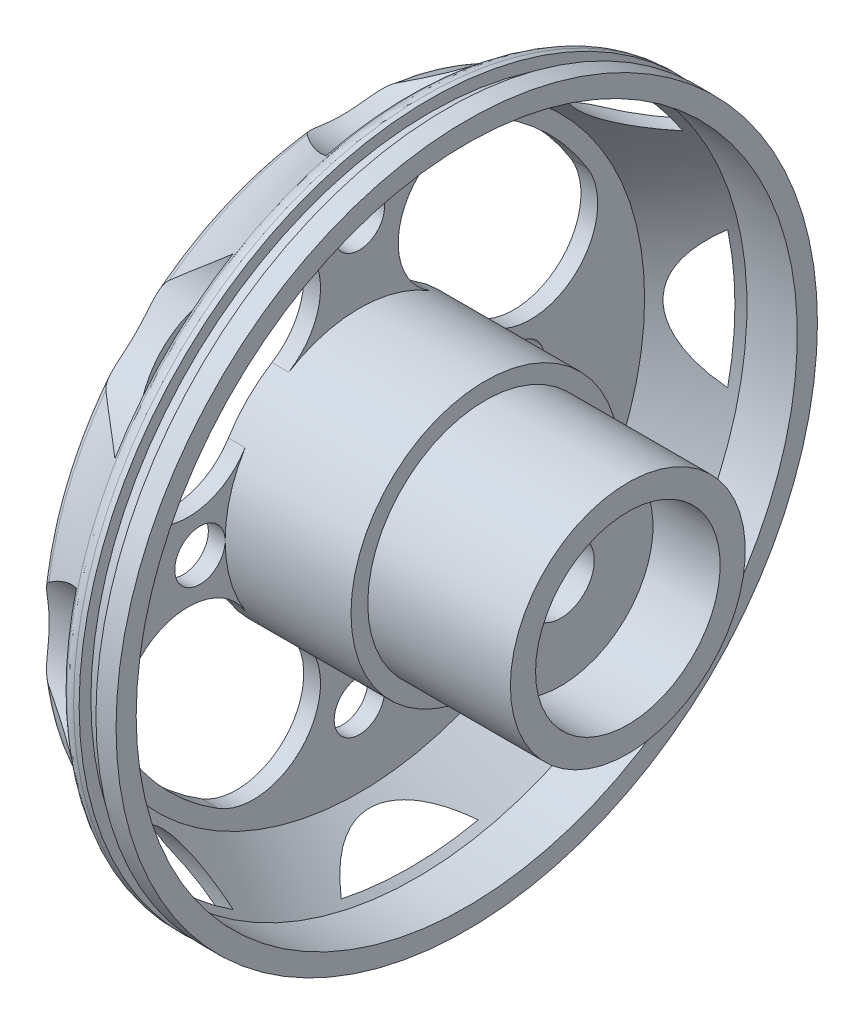
SolidWorks part; units mm, degrees
material "Aleación 1060"
ref_plane "Alzado" through (0, 0, 0) normal (0, 0, 1) x (1, 0, 0)
ref_plane "Planta" through (0, 0, 0) normal (0, 1, 0) x (1, 0, 0)
ref_plane "Vista lateral" through (0, 0, 0) normal (1, 0, 0) x (0, 0, -1)
sketch "Croquis1" plane through (0, 0, 0) normal (0, 0, 1) x (1, 0, 0)
  line L0 (0, 0) -> (0, 20.9) construction
  line L1 (0, 0) -> (19.6684, 0) construction
  line L2 (17, 5.5) -> (13, 5.5)
  line L3 (13, 5.5) -> (13, 2)
  line L4 (13, 2) -> (4, 2)
  line L5 (4, 2) -> (4, 5.5)
  line L6 (4, 5.5) -> (0, 5.5)
  line L7 (0, 5.5) -> (0, 18)
  line L8 (4.5, 20.9) -> (5.2, 20.9)
  line L9 (7.4, 20.9) -> (7.4, 19.7)
  line L10 (7.4, 19.7) -> (4.4, 19.7)
  line L11 (4.4, 19.7) -> (1, 17)
  line L12 (1, 17) -> (1, 8)
  line L13 (1, 8) -> (8.5, 8)
  line L14 (8.5, 8) -> (8.5, 7)
  line L15 (8.5, 7) -> (17, 7)
  line L16 (17, 7) -> (17, 5.5)
  line L17 (6.2, 20.9) -> (7.4, 20.9)
  line L19 (5.2, 20.9) -> (5.2, 20.2)
  line L20 (5.2, 20.2) -> (6.2, 20.2)
  line L21 (6.2, 20.9) -> (6.2, 20.2)
  arc A0 (0, 18) -> (4.5, 20.9) centre (-7.5237, 34.616) ccw
  dimension "D20" = 18.24
  dimension "D1" = 20.9
  dimension "D2" = 17
  dimension "D3" = 2
  dimension "D4" = 7
  dimension "D5" = 8
  dimension "D6" = 4
  dimension "D7" = 4.5
  dimension "D8" = 4
  dimension "D9" = 5.5
  dimension "D10" = 1
  dimension "D11" = 2.9
  dimension "D12" = 3
  dimension "D13" = 4.5
  dimension "D14" = 1.2
  dimension "D15" = 18
  dimension "D16" = 9
  dimension "D17" = 0.7
  dimension "D18" = 1
  dimension "D19" = 0.7
revolve "Revolución1" add sketch "Croquis1" angle 360 about L1
fillet "Redondeo1" radius 1 2 edges at (4.5, 0, 20.9) (0, 0, 18)
sketch "Croquis2" plane through (0, 0, 0) normal (-1, 0, 0) x (0, 0, 1)
  line L0 (0, 0) -> (0, 20.6649) construction
  line L1 (0, 0) -> (20.6649, 0) construction
  line L2 (0, 0) -> (14.6123, 14.6123) construction
  circle A0 centre (0, 0) radius 20.6649 construction
  arc A1 (6.3149, 10.204) -> (10.204, 6.3149) centre (0, 0) cw construction
  arc A2 (13.6053, 8.4199) -> (8.4199, 13.6053) centre (0, 0) ccw
  arc A3 (6.8027, 4.2099) -> (4.2099, 6.8027) centre (0, 0) ccw
  arc A4 (6.8027, 4.2099) -> (13.6053, 8.4199) centre (10.204, 6.3149) ccw
  arc A5 (8.4199, 13.6053) -> (4.2099, 6.8027) centre (6.3149, 10.204) ccw
  arc A6 (10.204, -6.3149) -> (6.3149, -10.204) centre (0, 0) cw construction
  arc A7 (8.4199, -13.6053) -> (13.6053, -8.4199) centre (0, 0) ccw
  arc A8 (4.2099, -6.8027) -> (6.8027, -4.2099) centre (0, 0) ccw
  arc A9 (4.2099, -6.8027) -> (8.4199, -13.6053) centre (6.3149, -10.204) ccw
  arc A10 (13.6053, -8.4199) -> (6.8027, -4.2099) centre (10.204, -6.3149) ccw
  arc A11 (-6.3149, -10.204) -> (-10.204, -6.3149) centre (0, 0) cw construction
  arc A12 (-13.6053, -8.4199) -> (-8.4199, -13.6053) centre (0, 0) ccw
  arc A13 (-6.8027, -4.2099) -> (-4.2099, -6.8027) centre (0, 0) ccw
  arc A14 (-6.8027, -4.2099) -> (-13.6053, -8.4199) centre (-10.204, -6.3149) ccw
  arc A15 (-8.4199, -13.6053) -> (-4.2099, -6.8027) centre (-6.3149, -10.204) ccw
  arc A16 (-10.204, 6.3149) -> (-6.3149, 10.204) centre (0, 0) cw construction
  arc A17 (-8.4199, 13.6053) -> (-13.6053, 8.4199) centre (0, 0) ccw
  arc A18 (-4.2099, 6.8027) -> (-6.8027, 4.2099) centre (0, 0) ccw
  arc A19 (-4.2099, 6.8027) -> (-8.4199, 13.6053) centre (-6.3149, 10.204) ccw
  arc A20 (-13.6053, 8.4199) -> (-6.8027, 4.2099) centre (-10.204, 6.3149) ccw
  arc A21 (10.5818, 18.0232) -> (18.0232, 10.5818) centre (16.9027, 16.9027) ccw
  circle A22 centre (0, 0) radius 20.9 construction
  arc A23 (20.2268, 5.2619) -> (20.2268, -5.2619) centre (23.9041, 0) ccw
  arc A24 (18.0232, -10.5818) -> (10.5818, -18.0232) centre (16.9027, -16.9027) ccw
  arc A25 (5.2619, -20.2268) -> (-5.2619, -20.2268) centre (0, -23.9041) ccw
  arc A26 (-10.5818, -18.0232) -> (-18.0232, -10.5818) centre (-16.9027, -16.9027) ccw
  arc A27 (-20.2268, -5.2619) -> (-20.2268, 5.2619) centre (-23.9041, 0) ccw
  arc A28 (-18.0232, 10.5818) -> (-10.5818, 18.0232) centre (-16.9027, 16.9027) ccw
  arc A29 (-5.2619, 20.2268) -> (5.2619, 20.2268) centre (0, 23.9041) ccw
  arc A30 (-20.2268, 5.2619) -> (-20.2268, -5.2619) centre (0, 0) ccw
  arc A31 (-18.0232, -10.5818) -> (-10.5818, -18.0232) centre (0, 0) ccw
  arc A32 (-5.2619, -20.2268) -> (5.2619, -20.2268) centre (0, 0) ccw
  arc A33 (10.5818, -18.0232) -> (18.0232, -10.5818) centre (0, 0) ccw
  arc A34 (20.2268, -5.2619) -> (20.2268, 5.2619) centre (0, 0) ccw
  arc A35 (18.0232, 10.5818) -> (10.5818, 18.0232) centre (0, 0) ccw
  arc A36 (5.2619, 20.2268) -> (-5.2619, 20.2268) centre (0, 0) ccw
  arc A37 (-10.5818, 18.0232) -> (-18.0232, 10.5818) centre (0, 0) ccw
  point P10 (8.4853, 8.4853)
  point P20 (8.4853, -8.4853)
  point P27 (-8.4853, -8.4853)
  point P34 (-8.4853, 8.4853)
  point P39 (0, 0)
  point P66 (0, 0)
  dimension "D3" = 16
  dimension "D4" = 8
  dimension "D1" = 45
  dimension "D2" = 5.5
  dimension "D5" = 4
  dimension "D6" = 8
extrude "Cortar-Extruir1" cut sketch "Croquis2" against normal blind 4
sketch "Croquis3" plane through (0, 0, 0) normal (-1, 0, 0) x (0, 0, 1)
  circle A0 centre (0, 0) radius 12.5
  circle A1 centre (0, 0) radius 9.5
  circle A2 centre (0, 12.5) radius 1.5
  circle A3 centre (0, -12.5) radius 1.5
  circle A4 centre (9.5, 0) radius 1.5
  circle A5 centre (-9.5, 0) radius 1.5
  dimension "D1" = 25
  dimension "D2" = 19
  dimension "D3" = 3
extrude "Cortar-Extruir2" cut sketch "Croquis3" against normal through all contours A0 A2 | A0 A2 | A1 A4 | A1 A4 | A5 | A3
